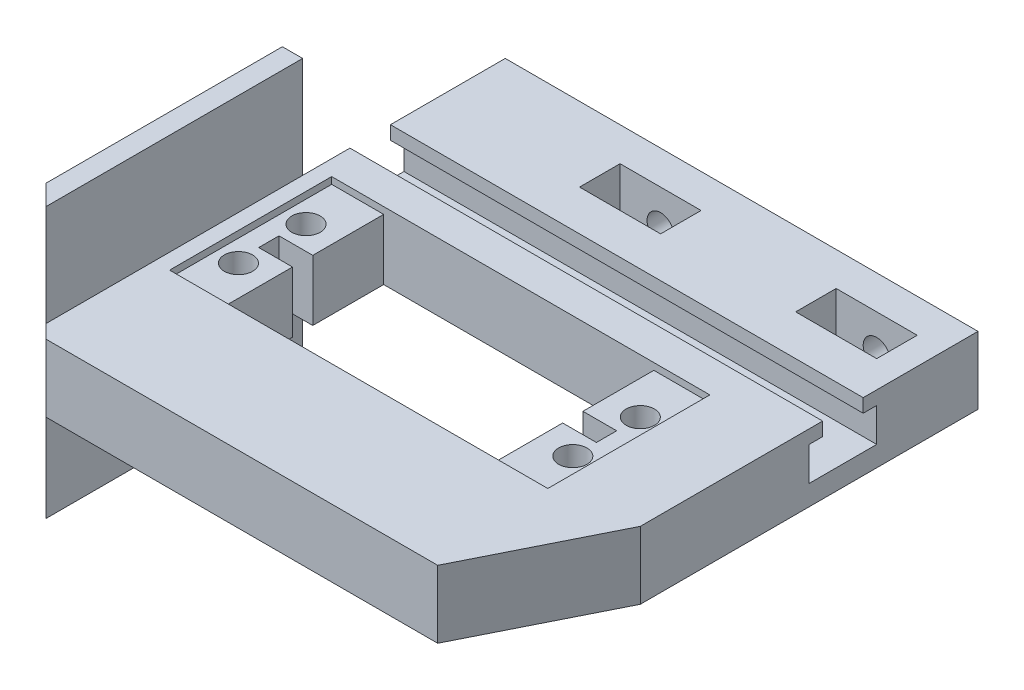
SolidWorks part; units mm, degrees
material "ABS"
ref_plane "前基準面" through (0, 0, 0) normal (0, 0, 1) x (1, 0, 0)
ref_plane "上基準面" through (0, 0, 0) normal (0, 1, 0) x (1, 0, 0)
ref_plane "右基準面" through (0, 0, 0) normal (1, 0, 0) x (0, 0, -1)
sketch "草圖1" plane through (0, 0, 0) normal (0, 1, 0) x (1, 0, 0)
  line L1 (-30, 12) -> (10, 12)
  line L2 (-30, 12) -> (-30, -12)
  line L3 (-30, -12) -> (10, -12)
  line L4 (10, 12) -> (10, -12)
  line L5 (-40, 30) -> (40, 30)
  line L6 (-40, 30) -> (-40, -30)
  line L7 (-40, -30) -> (40, -30)
  line L8 (40, 30) -> (40, -30)
  circle A0 centre (0, 0) radius 1.6622
  circle A1 centre (15, 5) radius 2.1
  circle A2 centre (15, -5) radius 2.1
  circle A3 centre (-34.5, 5) radius 2.1
  circle A4 centre (-34.5, -5) radius 2.1
  dimension "D4" = 4.2
  dimension "D5" = 4.2
  dimension "D6" = 4.2
  dimension "D7" = 4.2
  dimension "D1" = 10
  dimension "D2" = 15
  dimension "D3" = 5
  dimension "D8" = 49.5
  dimension "D9" = 49.5
  dimension "D10" = 40
  dimension "D11" = 5
  dimension "D12" = 24
  dimension "D13" = 12
  dimension "D14" = 30
  dimension "D15" = 30
  dimension "D16" = 40
  dimension "D17" = 40
extrude "填料-伸長1" add sketch "草圖1" along normal blind 10 contours L8 L5 L6 L7 A4 A3 A2 A1 L1 L4 L3 L2
sketch "草圖4" plane through (40, 0, 0) normal (1, 0, 0) x (0, 0, -1)
  line L1 (30, 10) -> (-30, 10) construction
  line L9 (17, 10) -> (17, 8)
  line L10 (17, 8) -> (15, 8)
  line L11 (15, 8) -> (15, 3)
  line L12 (15, 3) -> (25, 3)
  line L13 (25, 3) -> (25, 8)
  line L14 (25, 8) -> (23, 8)
  line L15 (23, 8) -> (23, 10)
  line L16 (23, 10) -> (17, 10)
  line L17 (30, 0) -> (-30, 0) construction
  line L18 (30, 10) -> (30, 0) construction
  dimension "D1" = 10
  dimension "D5" = 2
  dimension "D6" = 2
  dimension "D7" = 3
  dimension "D11" = 5
  dimension "D12" = 5
  dimension "D13" = 5
extrude "除料-伸長1" cut sketch "草圖4" against normal blind 80
sketch "草圖5" plane through (0, 10, 0) normal (0, 1, 0) x (1, 0, 0)
  line L8 (10, 1.5) -> (10, -1.5)
  line L9 (10, 12) -> (10, -12) construction
  line L10 (10, -1.5) -> (15, -1.5)
  line L11 (15, -1.5) -> (15, 1.5)
  line L12 (15, 1.5) -> (10, 1.5)
  line L13 (-30, 1.5) -> (-35, 1.5)
  line L14 (-30, 12) -> (-30, -12) construction
  line L15 (-35, 1.5) -> (-35, -1.5)
  line L16 (-35, -1.5) -> (-30, -1.5)
  line L17 (-30, -1.5) -> (-30, 1.5)
  line L18 (-40, 17) -> (40, 17) construction
  dimension "D3" = 3
  dimension "D1" = 5
  dimension "D2" = 3
  dimension "D4" = 5
  dimension "D5" = 15.5
extrude "除料-伸長2" cut sketch "草圖5" against normal blind 80
sketch "草圖7" plane through (0, 10, 0) normal (0, 1, 0) x (1, 0, 0)
  line L1 (-37.7, 12) -> (18.3, 12)
  line L2 (-37.7, 12) -> (-37.7, -12)
  line L3 (-37.7, -12) -> (18.3, -12)
  line L4 (18.3, 12) -> (18.3, -12)
  circle A0 centre (15, -5) radius 2.1 construction
  dimension "D1" = 24
  dimension "D3" = 56
  dimension "D4" = 3.3
extrude "除料-伸長3" cut sketch "草圖7" against normal blind 1 contours L1 L4 L3 L2
sketch "草圖8" plane through (-40, 0, 0) normal (-1, 0, 0) x (0, 0, 1)
  line L0 (30, 25) -> (30, -15)
  line L5 (30, -15) -> (-10, -15)
  line L6 (-10, -15) -> (-10, 25)
  line L7 (-10, 25) -> (30, 25)
  point P0 (30, 10)
  point P1 (30, 0)
  dimension "D1" = 40
  dimension "D2" = 40
  dimension "D3" = 15
extrude "填料-伸長2" add sketch "草圖8" along normal blind 3
sketch "草圖9" plane through (0, 10, 0) normal (0, 1, 0) x (1, 0, 0)
  line L0 (-40, -30) -> (40, -30) construction
  line L1 (40, 30) -> (30, 30)
  line L2 (40, 30) -> (40, -30)
  line L3 (40, -30) -> (30, -30)
  line L4 (30, 30) -> (30, -30)
  dimension "D1" = 10
extrude "除料-伸長4" cut sketch "草圖9" against normal blind 10
sketch "草圖22" plane through (0, 10, 0) normal (0, 1, 0) x (1, 0, 0)
  line L0 (-43, -25) -> (-43, -30)
  line L1 (-43, -30) -> (-43, 10) construction
  line L2 (-43, -30) -> (-38, -30)
  line L3 (-40, -30) -> (30, -30) construction
  line L4 (-38, -30) -> (-43, -25)
  dimension "D1" = 5
  dimension "D2" = 5
extrude "除料-伸長11" cut sketch "草圖22" against normal blind 28
sketch "草圖23" plane through (0, 25, 0) normal (0, 1, 0) x (1, 0, 0)
  line L0 (-43, -30) -> (-38, -30)
  line L1 (-38, -30) -> (30, -30) construction
  line L2 (-38, -30) -> (-43, -25)
  line L3 (-43, -30) -> (-43, 10) construction
  line L4 (-43, -25) -> (-43, -30)
  dimension "D1" = 5
  dimension "D2" = 5
extrude "除料-伸長12" cut sketch "草圖23" against normal blind 28
sketch "草圖24" plane through (-40, 0, 0) normal (-1, 0, 0) x (0, 0, 1)
  line L0 (-25, 3) -> (-25, 8) construction
  line L1 (-30, 10) -> (-40, 10)
  line L2 (-30, 10) -> (-30, 0)
  line L3 (-30, 0) -> (-40, 0)
  line L4 (-40, 10) -> (-40, 0)
  dimension "D1" = 15
extrude "填料-伸長3" add sketch "草圖24" against normal up to vertex (70 mm away)
sketch "草圖25" plane through (0, 10, 0) normal (0, 1, 0) x (1, 0, 0)
  line L0 (-40, 40) -> (-40, 23) construction
  line L1 (-18, 35) -> (-6, 35)
  line L2 (-18, 35) -> (-18, 29)
  line L3 (-18, 29) -> (-6, 29)
  line L4 (-6, 35) -> (-6, 29)
  line L5 (14, 35) -> (26, 35)
  line L6 (14, 35) -> (14, 29)
  line L7 (14, 29) -> (26, 29)
  line L8 (26, 35) -> (26, 29)
  line L9 (30, 40) -> (30, 23) construction
  line L10 (-40, 23) -> (30, 23) construction
  dimension "D1" = 6
  dimension "D2" = 6
  dimension "D3" = 12
  dimension "D4" = 12
  dimension "D5" = 22
  dimension "D6" = 4
  dimension "D7" = 6
  dimension "D8" = 6
extrude "除料-伸長13" cut sketch "草圖25" against normal blind 9
sketch "草圖26" plane through (0, 0, -40) normal (0, 0, -1) x (-1, 0, 0)
  line L0 (-30, 10) -> (-30, 0) construction
  circle A0 centre (-20, 4.7234) radius 2
  circle A1 centre (12, 4.7234) radius 2
  dimension "D1" = 32
  dimension "D2" = 4
  dimension "D3" = 4
  dimension "D4" = 10
extrude "除料-伸長14" cut sketch "草圖26" against normal blind 8
sketch "草圖27" plane through (0, 10, 0) normal (0, 1, 0) x (1, 0, 0)
  line L0 (30, -10) -> (20, -30)
  line L1 (30, 17) -> (30, -30) construction
  line L2 (-38, -30) -> (30, -30) construction
  line L3 (20, -30) -> (30, -30)
  line L4 (30, -30) -> (30, -10)
  dimension "D2" = 20
  dimension "D3" = 10
extrude "除料-伸長15" cut sketch "草圖27" against normal up to next
